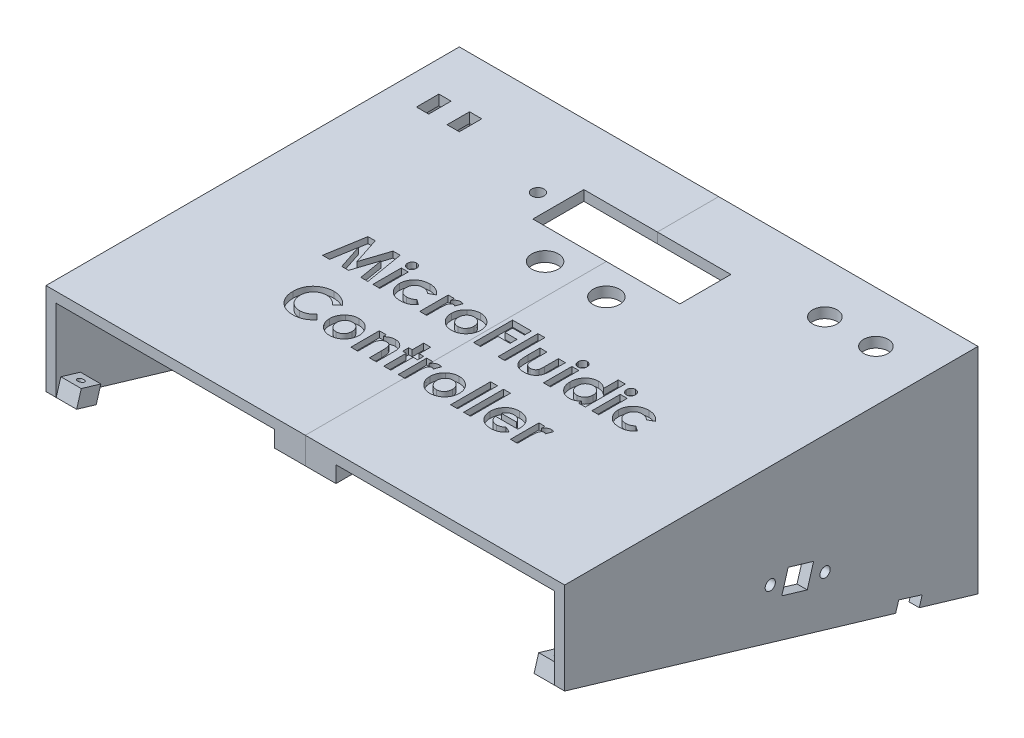
SolidWorks part; units mm, degrees
ref_plane "Front Plane" through (0, 0, 0) normal (0, 0, 1) x (1, 0, 0)
ref_plane "Top Plane" through (0, 0, 0) normal (0, 1, 0) x (1, 0, 0)
ref_plane "Right Plane" through (0, 0, 0) normal (1, 0, 0) x (0, 0, -1)
sketch "Sketch1" plane through (0, 0, 0) normal (0, 1, 0) x (1, 0, 0)
  line L1 (-127, -101.2) -> (127, -101.2)
  line L2 (-127, -101.2) -> (-127, 101.2)
  line L3 (-127, 101.2) -> (127, 101.2)
  line L4 (127, -101.2) -> (127, 101.2)
  line L5 (-127, -101.2) -> (127, 101.2) construction
  line L6 (-127, 101.2) -> (127, -101.2) construction
  point P0 (0, 0)
  dimension "D1" = 254
  dimension "D2" = 202.4
extrude "Boss-Extrude1" add sketch "Sketch1" along normal blind 5
sketch "Sketch2" plane through (0, 5, 0) normal (0, 1, 0) x (1, 0, 0)
  line L0 (0, 101.2) -> (0, -101.2) construction
  line L1 (127, 101.2) -> (-127, 101.2) construction
  line L2 (-127, -101.2) -> (127, -101.2) construction
  line L3 (-127, 0) -> (127, 0) construction
  line L4 (-127, 101.2) -> (-127, -101.2) construction
  line L5 (127, -101.2) -> (127, 101.2) construction
  line L7 (-36, 46.2) -> (36, 46.2)
  line L8 (-36, 46.2) -> (-36, 71.2)
  line L9 (-36, 71.2) -> (36, 71.2)
  line L10 (36, 46.2) -> (36, 71.2)
  line L11 (-36, 46.2) -> (36, 71.2) construction
  line L12 (-36, 71.2) -> (36, 46.2) construction
  point P12 (0, 58.7)
  dimension "D1" = 25
  dimension "D2" = 72
  dimension "D3" = 30
extrude "Cut-Extrude1" cut sketch "Sketch2" against normal blind 10
sketch "Sketch3" plane through (0, 5, 0) normal (0, 1, 0) x (1, 0, 0)
  line L0 (127, 101.2) -> (-127, 101.2) construction
  line L1 (127, -101.2) -> (127, 101.2) construction
  circle A0 centre (77, 76.2) radius 6
  circle A1 centre (102, 76.2) radius 6
  dimension "D1" = 12
  dimension "D2" = 25
  dimension "D3" = 50
  dimension "D4" = 2
extrude "Cut-Extrude2" cut sketch "Sketch3" against normal blind 10
sketch "Sketch4" plane through (0, 5, 0) normal (0, 1, 0) x (1, 0, 0)
  line L0 (127, 101.2) -> (-127, 101.2) construction
  line L1 (-112, 76.2) -> (-106, 76.2)
  line L2 (-112, 76.2) -> (-112, 65.2)
  line L3 (-112, 65.2) -> (-106, 65.2)
  line L4 (-106, 76.2) -> (-106, 65.2)
  line L5 (-112, 76.2) -> (-106, 65.2) construction
  line L6 (-112, 65.2) -> (-106, 76.2) construction
  line L7 (-127, 101.2) -> (-127, -101.2) construction
  line L8 (-91, 76.2) -> (-91, 65.2)
  line L9 (-97, 76.2) -> (-91, 76.2)
  line L10 (-97, 76.2) -> (-97, 65.2)
  line L11 (-97, 65.2) -> (-91, 65.2)
  point P0 (-109, 70.7)
  dimension "D1" = 11
  dimension "D2" = 6
  dimension "D3" = 25
  dimension "D4" = 15
  dimension "D5" = 2
extrude "Cut-Extrude3" cut sketch "Sketch4" against normal blind 10
sketch "Sketch5" plane through (0, 5, 0) normal (0, 1, 0) x (1, 0, 0)
  line L0 (0, -2.75) -> (0, 2.75) construction
  line L1 (-36, 46.2) -> (36, 46.2) construction
  line L2 (-36, 71.2) -> (-36, 46.2) construction
  circle A0 centre (-15, 31.2) radius 6.5
  circle A1 centre (15, 31.2) radius 6.5
  circle A2 centre (-46, 58.7) radius 3
  point P12 (-36, 58.7)
  dimension "D1" = 13
  dimension "D2" = 13
  dimension "D8" = 6
  dimension "D3" = 30
  dimension "D4" = 15
  dimension "D5" = 15
  dimension "D6" = 0
  dimension "D7" = 10
extrude "Cut-Extrude4" cut sketch "Sketch5" against normal blind 10
sketch "Sketch6" plane through (0, 5, 0) normal (0, 1, 0) x (1, 0, 0)
  text T0 "MicroFluidic \r\n Controller" font "Century Gothic" height in points 72
extrude "Cut-Extrude5" cut sketch "Sketch6" against normal blind 3
sketch "Sketch7" plane through (0, 0, 0) normal (0, -1, 0) x (1, 0, 0)
  line L0 (-127, 101.2) -> (127, 101.2) construction
  line L1 (15, 61.2) -> (-15, 61.2)
  line L2 (15, 61.2) -> (15, 101.2)
  line L3 (15, 101.2) -> (-15, 101.2)
  line L4 (-15, 61.2) -> (-15, 101.2)
  line L5 (15, 61.2) -> (-15, 101.2) construction
  line L6 (15, 101.2) -> (-15, 61.2) construction
  line L7 (0, -2.75) -> (0, 2.75) construction
  line L8 (127, -101.2) -> (-127, -101.2) construction
  line L9 (15, -81.2) -> (-15, -81.2)
  line L10 (15, -81.2) -> (15, -101.2)
  line L11 (15, -101.2) -> (-15, -101.2)
  line L12 (-15, -81.2) -> (-15, -101.2)
  line L13 (15, -81.2) -> (-15, -101.2) construction
  line L14 (15, -101.2) -> (-15, -81.2) construction
  point P0 (0, 81.2)
  point P9 (0, -91.2)
  dimension "D1" = 40
  dimension "D2" = 30
  dimension "D3" = 15
  dimension "D4" = 20
  dimension "D5" = 30
extrude "Boss-Extrude2" add sketch "Sketch7" along normal blind 8
sketch "Sketch9" plane through (15, 0, 0) normal (1, 0, 0) x (0, 0, -1)
  line L0 (101.2, -8) -> (81.2, -8) construction
  line L1 (-101.2, -8) -> (-101.2, 0) construction
  circle A0 centre (89.5846, -4) radius 1.75
  circle A1 centre (-91.2, -4) radius 1.75
  circle A2 centre (-71.2, -4) radius 1.75
  dimension "D1" = 3.5
  dimension "D2" = 4
  dimension "D3" = 3.5
  dimension "D4" = 3.5
  dimension "D5" = 20
  dimension "D6" = 10
extrude "Cut-Extrude6" cut sketch "Sketch9" against normal blind 40
sketch "Sketch10" plane through (127, 0, 0) normal (1, 0, 0) x (0, 0, -1)
  line L0 (101.2, 0) -> (101.2, -100)
  line L1 (101.2, -100) -> (-101.2, -40)
  line L2 (-101.2, -40) -> (-101.2, 0)
  line L3 (-101.2, 0) -> (101.2, 0)
  dimension "D1" = 100
  dimension "D2" = 40
extrude "Boss-Extrude3" add sketch "Sketch10" against normal blind 5
sketch "Sketch11" plane through (-127, 0, 0) normal (-1, 0, 0) x (0, 0, 1)
  line L0 (101.2, 0) -> (101.2, -40)
  line L1 (101.2, -40) -> (-101.2, -100)
  line L2 (-101.2, -100) -> (-101.2, 0)
  line L3 (-101.2, 0) -> (101.2, 0)
  dimension "D1" = 40
  dimension "D2" = 100
extrude "Boss-Extrude4" add sketch "Sketch11" against normal blind 5
sketch "Sketch12" plane through (0, -64.3454, 19.0747) normal (0, -0.9588, 0.2842) x (1, 0, 0)
  line L0 (0, -130.3205) -> (0, 193.6602) construction
  line L1 (-112, 85.6578) -> (-112, 75.6578)
  line L2 (122, -125.4482) -> (112, -125.4482)
  line L3 (122, -125.4482) -> (122, -115.4482)
  line L4 (122, -115.4482) -> (112, -115.4482)
  line L5 (112, -125.4482) -> (112, -115.4482)
  line L6 (122, 85.6578) -> (112, 85.6578)
  line L7 (122, 85.6578) -> (122, 75.6578)
  line L8 (122, 75.6578) -> (112, 75.6578)
  line L9 (112, 85.6578) -> (112, 75.6578)
  line L10 (-122, 85.6578) -> (-112, 85.6578)
  line L11 (-122, 85.6578) -> (-122, 75.6578)
  line L12 (-122, 75.6578) -> (-112, 75.6578)
  line L13 (-122, -115.4482) -> (-112, -115.4482)
  line L14 (-112, -125.4482) -> (-112, -115.4482)
  line L15 (-122, -125.4482) -> (-112, -125.4482)
  line L16 (-122, -125.4482) -> (-122, -115.4482)
  circle A0 centre (117, -120.4482) radius 1.6
  circle A1 centre (117, 80.6578) radius 1.6
  circle A2 centre (-117, 80.6578) radius 1.6
  circle A3 centre (-117, -120.4482) radius 1.6
  dimension "D5" = 3.2
  dimension "D6" = 3.2
  dimension "D1" = 10
  dimension "D2" = 10
  dimension "D3" = 10
  dimension "D4" = 10
extrude "Boss-Extrude5" add sketch "Sketch12" against normal blind 8
sketch "Sketch13" plane through (127, 0, 0) normal (1, 0, 0) x (0, 0, -1)
  line L0 (60.8758, -88.0462) -> (62.3935, -83.136)
  line L1 (-101.2, -40) -> (101.2, -100) construction
  line L2 (62.3935, -83.136) -> (73.8583, -86.6797)
  line L3 (73.8583, -86.6797) -> (72.4372, -91.4735)
  line L4 (72.4372, -91.4735) -> (60.8758, -88.0462)
  line L5 (5.1093, -52.7646) -> (17.5732, -56.4594)
  line L6 (5.1093, -52.7646) -> (8.2357, -42.2182)
  line L7 (17.5732, -56.4594) -> (20.6996, -45.913)
  line L8 (8.2357, -42.2182) -> (20.6996, -45.913)
  circle A0 centre (26.3271, -53.3178) radius 2.5
  circle A1 centre (-0.5182, -45.3598) radius 2.5
  dimension "D6" = 5
  dimension "D7" = 5
  dimension "D1" = 12
  dimension "D2" = 5
  dimension "D3" = 30
  dimension "D4" = 11
  dimension "D5" = 13
  dimension "D8" = 7.5
  dimension "D9" = 7.5
extrude "Cut-Extrude7" cut sketch "Sketch13" against normal blind 10
sketch "Sketch16" plane through (0, 5, 0) normal (0, 1, 0) x (1, 0, 0)
  line L0 (0, 153.0371) -> (0, -199.5202)
split "Split1" trim tools "Sketch16" bodies to split 112 resulting bodies 113 114
